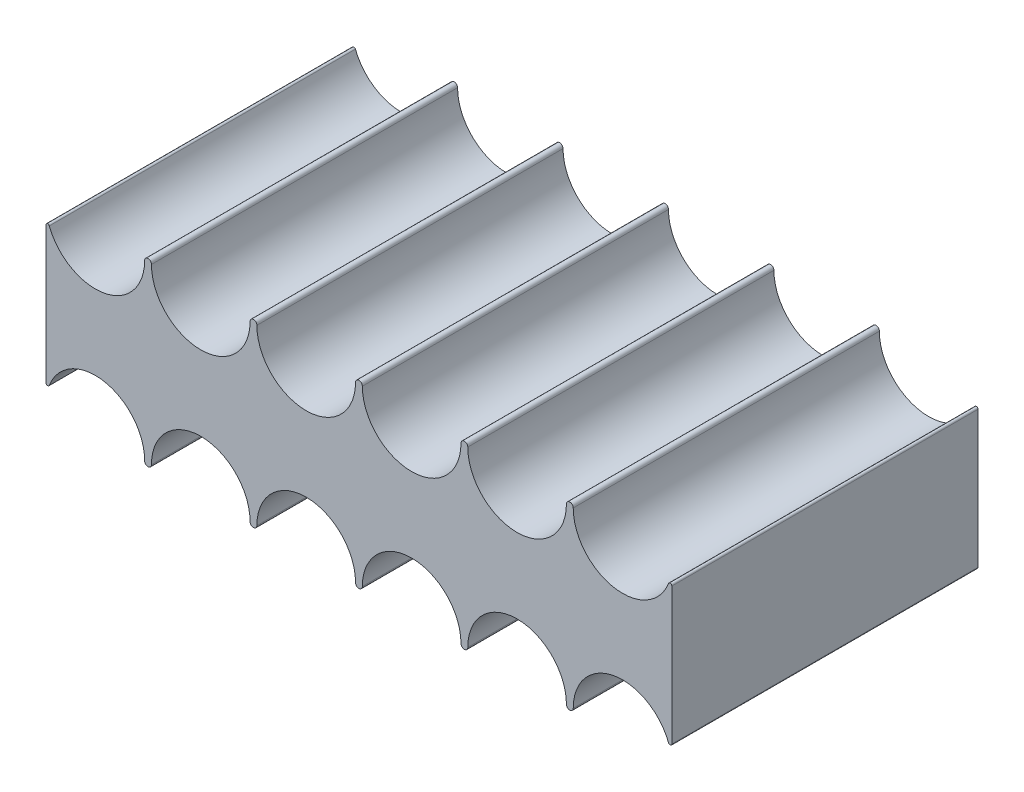
SolidWorks part; units mm, degrees
ref_plane "Front Plane" through (0, 0, 0) normal (0, 0, 1) x (1, 0, 0)
ref_plane "Top Plane" through (0, 0, 0) normal (0, 1, 0) x (1, 0, 0)
ref_plane "Right Plane" through (0, 0, 0) normal (1, 0, 0) x (0, 0, -1)
sketch "Esquisse1" plane through (0, 0, 0) normal (0, 0, 1) x (1, 0, 0)
  line L0 (-46, 0) -> (46, 0) construction
  line L1 (-46, 10.0574) -> (-46, -10.0574)
  line L2 (0, 9.3907) -> (0, -12.68) construction
  line L3 (46, 10.0574) -> (46, -10.0574)
  arc A0 (-45.5167, 10.1472) -> (-31.5, 12.75) centre (-38.75, 12.75) ccw
  arc A1 (-30.5, 12.75) -> (-16, 12.75) centre (-23.25, 12.75) ccw
  arc A2 (-15, 12.75) -> (-0.5, 12.75) centre (-7.75, 12.75) ccw
  arc A3 (0.5, 12.75) -> (15, 12.75) centre (7.75, 12.75) ccw
  arc A4 (16, 12.75) -> (30.5, 12.75) centre (23.25, 12.75) ccw
  arc A5 (31.5, 12.75) -> (45.5167, 10.1472) centre (38.75, 12.75) ccw
  arc A6 (45.5167, 10.1472) -> (46, 10.0574) centre (45.75, 10.0574) cw
  arc A7 (-45.5167, 10.1472) -> (-46, 10.0574) centre (-45.75, 10.0574) ccw
  arc A8 (-31.5, 12.75) -> (-30.5, 12.75) centre (-31, 12.75) cw
  arc A9 (-16, 12.75) -> (-15, 12.75) centre (-15.5, 12.75) cw
  arc A10 (-0.5, 12.75) -> (0.5, 12.75) centre (0, 12.75) cw
  arc A11 (15, 12.75) -> (16, 12.75) centre (15.5, 12.75) cw
  arc A12 (30.5, 12.75) -> (31.5, 12.75) centre (31, 12.75) cw
  arc A13 (30.5, -12.75) -> (31.5, -12.75) centre (31, -12.75) ccw
  arc A14 (15, -12.75) -> (16, -12.75) centre (15.5, -12.75) ccw
  arc A15 (-0.5, -12.75) -> (0.5, -12.75) centre (0, -12.75) ccw
  arc A16 (-16, -12.75) -> (-15, -12.75) centre (-15.5, -12.75) ccw
  arc A17 (-31.5, -12.75) -> (-30.5, -12.75) centre (-31, -12.75) ccw
  arc A18 (-45.5167, -10.1472) -> (-46, -10.0574) centre (-45.75, -10.0574) cw
  arc A19 (45.5167, -10.1472) -> (46, -10.0574) centre (45.75, -10.0574) ccw
  arc A20 (31.5, -12.75) -> (45.5167, -10.1472) centre (38.75, -12.75) cw
  arc A21 (16, -12.75) -> (30.5, -12.75) centre (23.25, -12.75) cw
  arc A22 (0.5, -12.75) -> (15, -12.75) centre (7.75, -12.75) cw
  arc A23 (-15, -12.75) -> (-0.5, -12.75) centre (-7.75, -12.75) cw
  arc A24 (-30.5, -12.75) -> (-16, -12.75) centre (-23.25, -12.75) cw
  arc A25 (-45.5167, -10.1472) -> (-31.5, -12.75) centre (-38.75, -12.75) cw
  point P25 (46, 12.75)
  point P28 (-46, 12.75)
  point P61 (-46, -12.75)
  point P62 (46, -12.75)
  dimension "D2" = 7.25
  dimension "D5" = 0.25
  dimension "D1" = 92
  dimension "D3" = 12.75
  dimension "D4" = 6
extrude "Boss.-Extru.1" add sketch "Esquisse1" along normal blind 45
